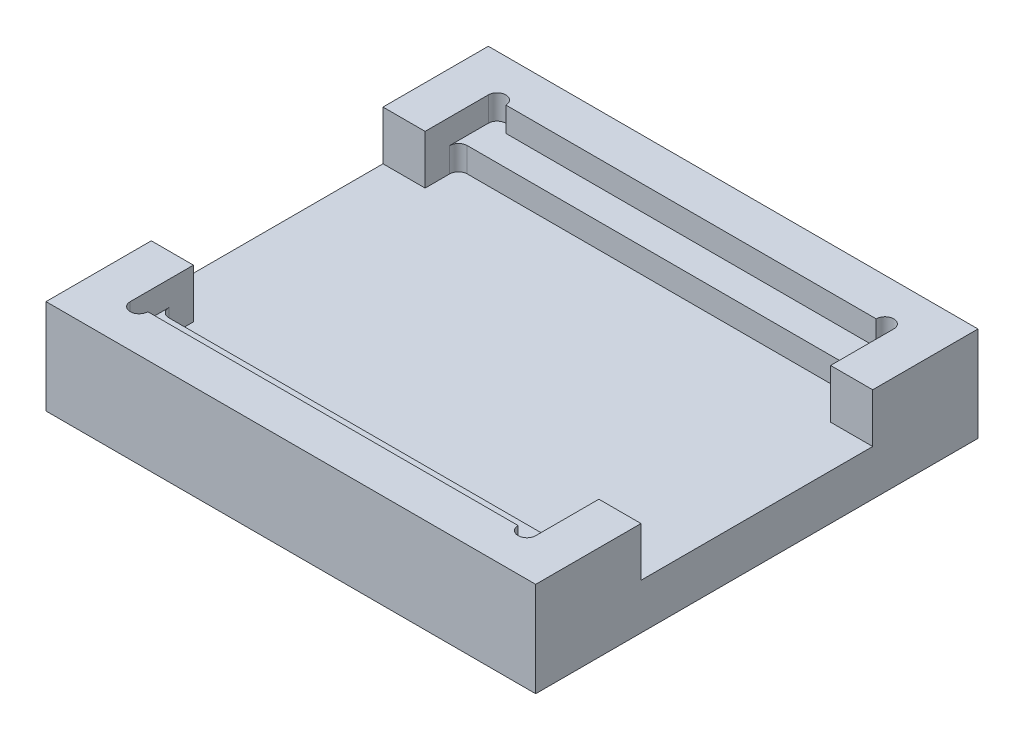
SolidWorks part; units mm, degrees
material "Delrin 2700 NC010, Low Viscosity Acetal Copolymer (SS)"
ref_plane "Front Plane" through (0, 0, 0) normal (0, 0, 1) x (1, 0, 0)
ref_plane "Top Plane" through (0, 0, 0) normal (0, 1, 0) x (1, 0, 0)
ref_plane "Right Plane" through (0, 0, 0) normal (1, 0, 0) x (0, 0, -1)
sketch "Sketch1" plane through (0, 0, 0) normal (0, 1, 0) x (1, 0, 0)
  line L1 (0, 0) -> (139.5, 0)
  line L2 (0, 0) -> (0, 126)
  line L3 (0, 126) -> (139.5, 126)
  line L4 (139.5, 0) -> (139.5, 126)
  dimension "D1" = 126
  dimension "D2" = 139.5
extrude "Boss-Extrude1" add sketch "Sketch1" along normal blind 27
sketch "Sketch2" plane through (0, 27, 0) normal (0, 1, 0) x (1, 0, 0)
  line L0 (0, 126) -> (0, 0) construction
  line L1 (12, 114) -> (127.5, 114)
  line L2 (12, 114) -> (12, 12)
  line L3 (12, 12) -> (127.5, 12)
  line L4 (127.5, 114) -> (127.5, 12)
  line L5 (0, 0) -> (139.5, 0) construction
  line L6 (139.5, 0) -> (139.5, 126) construction
  line L7 (139.5, 126) -> (0, 126) construction
  dimension "D1" = 12
  dimension "D2" = 12
  dimension "D3" = 12
  dimension "D4" = 12
extrude "Cut-Extrude1" cut sketch "Sketch2" against normal blind 7
sketch "Sketch3" plane through (0, 20, 0) normal (0, 1, 0) x (1, 0, 0)
  line L1 (127.5, 105.5) -> (12, 105.5)
  line L2 (127.5, 105.5) -> (127.5, 20.5)
  line L3 (127.5, 20.5) -> (12, 20.5)
  line L4 (12, 105.5) -> (12, 20.5)
  line L5 (127.5, 114) -> (12, 114) construction
  line L6 (12, 114) -> (12, 12) construction
  line L7 (127.5, 12) -> (127.5, 114) construction
  line L8 (12, 12) -> (127.5, 12) construction
  dimension "D1" = 8.5
  dimension "D3" = 8.5
extrude "Cut-Extrude2" cut sketch "Sketch3" against normal blind 7
sketch "Sketch4" plane through (0, 27, 0) normal (0, 1, 0) x (1, 0, 0)
  line L0 (0, 126) -> (0, 0) construction
  line L1 (0, 30) -> (12, 30)
  line L2 (0, 30) -> (0, 96)
  line L3 (0, 96) -> (12, 96)
  line L4 (12, 30) -> (12, 96)
  line L5 (12, 114) -> (12, 12) construction
  line L6 (0, 0) -> (139.5, 0) construction
  line L7 (139.5, 126) -> (0, 126) construction
  dimension "D1" = 30
  dimension "D2" = 30
extrude "Cut-Extrude3" cut sketch "Sketch4" against normal blind 14
sketch "Sketch5" plane through (0, 27, 0) normal (0, 1, 0) x (1, 0, 0)
  line L0 (139.5, 0) -> (139.5, 126) construction
  line L1 (139.5, 96) -> (127.5, 96)
  line L2 (139.5, 96) -> (139.5, 30)
  line L3 (139.5, 30) -> (127.5, 30)
  line L4 (127.5, 96) -> (127.5, 30)
  line L5 (127.5, 12) -> (127.5, 114) construction
  line L6 (0, 0) -> (139.5, 0) construction
  line L7 (139.5, 126) -> (0, 126) construction
  dimension "D1" = 30
  dimension "D2" = 30
extrude "Cut-Extrude4" cut sketch "Sketch5" against normal blind 14
sketch "Sketch6" plane through (0, 27, 0) normal (0, 1, 0) x (1, 0, 0)
  line L2 (12, 12) -> (127.5, 12) construction
  line L3 (12, 12) -> (17, 12)
  line L4 (12, 12) -> (127.5, 12) construction
  line L5 (122.5, 12) -> (127.5, 12)
  line L6 (127.5, 114) -> (12, 114) construction
  line L7 (12, 114) -> (17, 114)
  line L8 (122.5, 114) -> (127.5, 114)
  arc A1 (12, 12) -> (17, 12) centre (14.5, 12) ccw
  arc A2 (127.5, 12) -> (122.5, 12) centre (125, 12) cw
  arc A3 (12, 114) -> (17, 114) centre (14.5, 114) cw
  arc A4 (127.5, 114) -> (122.5, 114) centre (125, 114) ccw
  dimension "D1" = 2.5
  dimension "D2" = 2.5
  dimension "D3" = 2.5
  dimension "D4" = 2.5
extrude "Cut-Extrude5" cut sketch "Sketch6" against normal up to surface (7 mm away) up to face at (69.75, 20, -16.25)
fillet "Fillet1" radius 2.5 4 edges at (127.5, 16.5, -20.5) (127.5, 16.5, -105.5) (12, 16.5, -20.5) (12, 16.5, -105.5)
